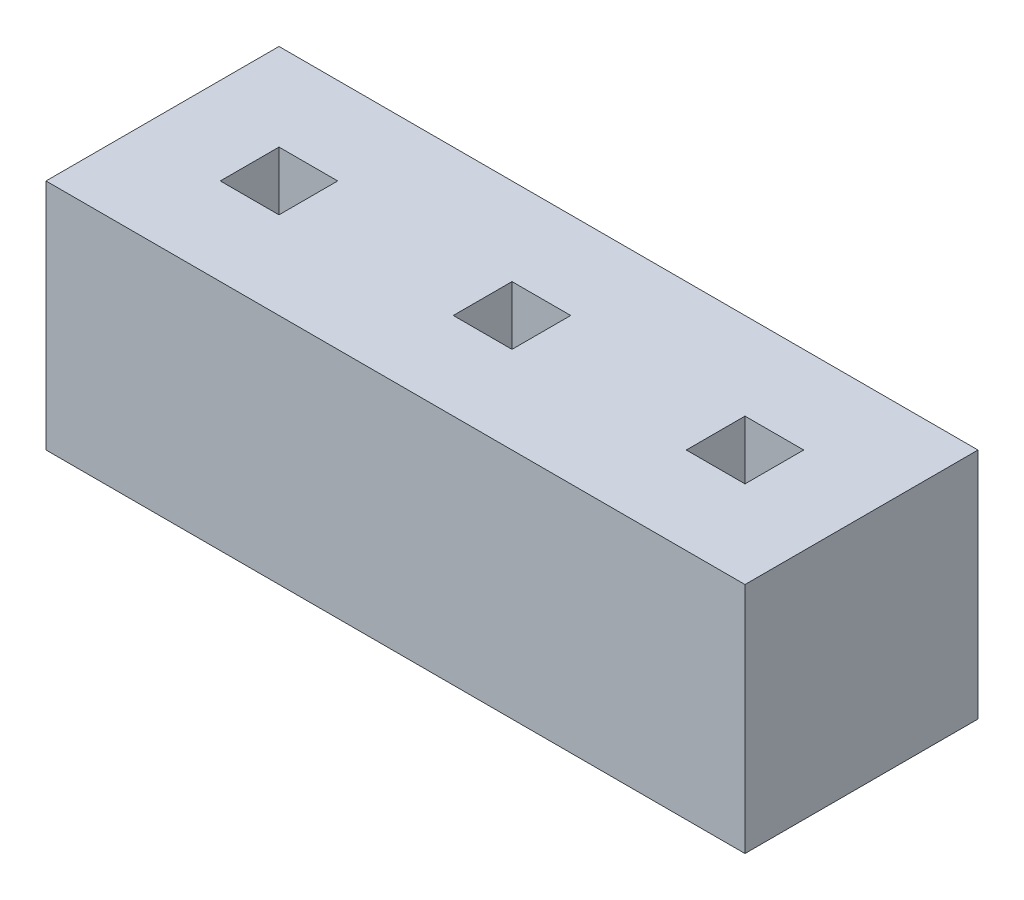
SolidWorks part; units mm, degrees
ref_plane "Front Plane" through (0, 0, 0) normal (0, 0, 1) x (1, 0, 0)
ref_plane "Top Plane" through (0, 0, 0) normal (0, 1, 0) x (1, 0, 0)
ref_plane "Right Plane" through (0, 0, 0) normal (1, 0, 0) x (0, 0, -1)
sketch "Sketch2" plane through (0, 0, 0) normal (0, 1, 0) x (1, 0, 0)
  line L1 (-3.81, -1.27) -> (3.81, -1.27)
  line L2 (-3.81, -1.27) -> (-3.81, 1.27)
  line L3 (-3.81, 1.27) -> (3.81, 1.27)
  line L4 (3.81, -1.27) -> (3.81, 1.27)
  line L5 (-3.81, -1.27) -> (3.81, 1.27) construction
  line L6 (-3.81, 1.27) -> (3.81, -1.27) construction
  point P0 (0, 0)
  dimension "D1" = 7.62
  dimension "D2" = 2.54
extrude "Boss-Extrude1" add sketch "Sketch2" along normal blind 2.54
sketch "Sketch3" plane through (0, 2.54, 0) normal (0, 1, 0) x (1, 0, 0)
  line L1 (-0.32, -0.32) -> (0.32, -0.32)
  line L2 (-0.32, -0.32) -> (-0.32, 0.32)
  line L3 (-0.32, 0.32) -> (0.32, 0.32)
  line L4 (0.32, -0.32) -> (0.32, 0.32)
  line L5 (-0.32, -0.32) -> (0.32, 0.32) construction
  line L6 (-0.32, 0.32) -> (0.32, -0.32) construction
  line L7 (-2.86, -0.32) -> (-2.22, -0.32)
  line L8 (-2.86, -0.32) -> (-2.86, 0.32)
  line L9 (-2.86, 0.32) -> (-2.22, 0.32)
  line L10 (-2.22, -0.32) -> (-2.22, 0.32)
  line L11 (-2.86, -0.32) -> (-2.22, 0.32) construction
  line L12 (-2.86, 0.32) -> (-2.22, -0.32) construction
  line L13 (2.22, -0.32) -> (2.86, -0.32)
  line L14 (2.22, -0.32) -> (2.22, 0.32)
  line L15 (2.22, 0.32) -> (2.86, 0.32)
  line L16 (2.86, -0.32) -> (2.86, 0.32)
  line L17 (2.22, -0.32) -> (2.86, 0.32) construction
  line L18 (2.22, 0.32) -> (2.86, -0.32) construction
  point P0 (0, 0)
  point P6 (-2.54, 0)
  point P11 (2.54, 0)
  dimension "D1" = 0.64
  dimension "D2" = 0.64
  dimension "D3" = 2.54
  dimension "D4" = 2.54
extrude "Cut-Extrude1" cut sketch "Sketch3" against normal through all
